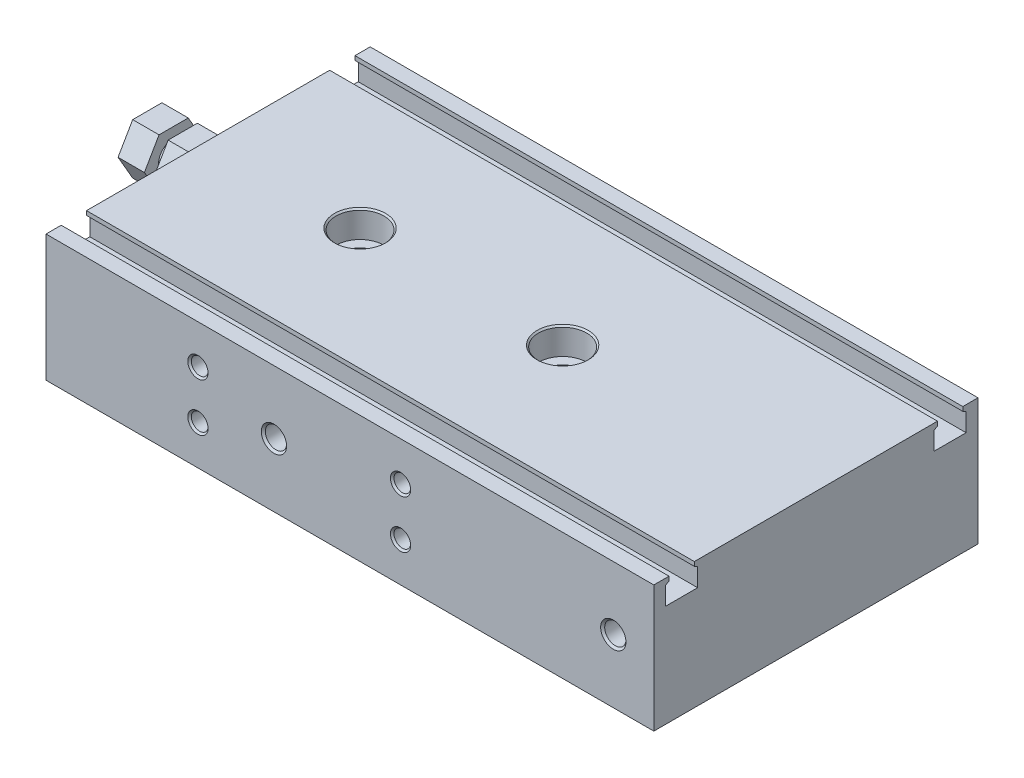
SolidWorks part; units mm, degrees
ref_plane "Plane1" through (0, 0, 0) normal (0, 0, 1) x (1, 0, 0)
ref_plane "Plane2" through (0, 0, 0) normal (0, 1, 0) x (1, 0, 0)
ref_plane "Plane3" through (0, 0, 0) normal (1, 0, 0) x (0, 0, -1)
sketch "Body_Sketch" plane through (0, 0, 0) normal (1, 0, 0) x (0, 0, -1)
  line L0 (-32, 12.5) -> (-32, -12.5)
  line L1 (-32, -12.5) -> (32, -12.5)
  line L2 (32, -12.5) -> (32, 12.5)
  line L3 (32, 12.5) -> (-32, 12.5)
  line L4 (-25.3, 0) -> (25.3, 0) construction
  line L5 (0, -7.85) -> (0, 10.85) construction
  line L6 (27.956, 0) -> (-27.956, 0) construction
  line L7 (0, 12.3416) -> (0, -12.3416) construction
  dimension "A" = 64
  dimension "B" = 25
  dimension "QQ" = 12.5
extrude "Body" add sketch "Body_Sketch" along normal blind 120
sketch "Body Bot Grooves_Sketch" [suppressed] plane through (0, 0, 0) normal (1, 0, 0) x (0, 0, -1)
  line L0 (0, 0) -> (0, -14.4793) construction
  line L1 (-12, -6.5) -> (-4, -6.5)
  line L2 (-4, -6.5) -> (-5, -5.5)
  line L3 (-5, -5.5) -> (-11, -5.5)
  line L4 (-11, -5.5) -> (-12, -6.5)
  line L5 (-8, -5.5) -> (-8, -12.5787) construction
  line L6 (18.5, 10) -> (-18.5, 10) construction
  line L7 (11, -5.5) -> (12, -6.5)
  line L8 (5, -5.5) -> (11, -5.5)
  line L9 (4, -6.5) -> (5, -5.5)
  line L10 (12, -6.5) -> (4, -6.5)
  dimension "Angle" = 45
  dimension "Raw Height" = 16.5
  dimension "Loc Y" = 15.5
  dimension "Width" = 8
  dimension "C2C" = 16
extrude "Body Bot Grooves" [suppressed] cut sketch "Body Bot Grooves_Sketch" along normal through all
sketch "Body Rod Holes_Sketch" plane through (0, 0, 0) normal (-1, 0, 0) x (0, 0, 1)
  line L0 (27.956, 0) -> (-27.956, 0) construction
  line L1 (0, 11.1009) -> (0, -8.2638) construction
  line L2 (0, -12.3416) -> (0, 12.3416) construction
  circle A0 centre (-14, 0) radius 5
  circle A1 centre (14, 0) radius 5
  dimension "NN" = 10
  dimension "H" = 28
extrude "Body Rod Holes" cut sketch "Body Rod Holes_Sketch" against normal blind 10
sketch "Body Piston Holes_Sketch" plane through (10, 0, 0) normal (-1, 0, 0) x (0, 0, 1)
  circle A0 centre (14, 0) radius 6.05
  circle A1 centre (-14, 0) radius 6.05
extrude "Body Piston Holes" cut sketch "Body Piston Holes_Sketch" against normal blind 51
sketch "Body Thru Hole_Sketch" [suppressed] plane through (0, 0, 0) normal (1, 0, 0) x (0, 0, -1)
  line L0 (0, 0) -> (0, -9.4152) construction
  line L1 (11.5, -6) -> (18.5, -6) construction
  circle A0 centre (14.95, -3) radius 1.4
  dimension "Dia" = 2.8
  dimension "Loc Y" = 3
  dimension "Loc Z" = 14.95
extrude "Body Thru Hole" [suppressed] cut sketch "Body Thru Hole_Sketch" along normal through all
sketch "Bot Switch Groove_Sketch" [suppressed] plane through (0, 0, 0) normal (1, 0, 0) x (0, 0, -1)
  line L0 (0, 0) -> (0, -12.0384) construction
  line L1 (1.6, -6.5) -> (-1.6, -6.5)
  line L2 (-1.6, -6.5) -> (-1.6, -3)
  line L3 (-1.6, -3) -> (-2.8, -3)
  line L4 (-2.8, -3) -> (-2.8, 0)
  line L5 (-2.8, 0) -> (2.8, 0)
  line L6 (2.8, -3) -> (2.8, 0)
  line L7 (-12, -6.5) -> (-4, -6.5) construction
  line L8 (1.6, -3) -> (2.8, -3)
  line L10 (1.6, -6.5) -> (1.6, -3)
  point P12 (0, 0)
  point P15 (0, -6.5)
  dimension "Bot Height" = 3.5
  dimension "Top Height" = 3
  dimension "Bot Width" = 3.2
  dimension "Top Width" = 5.6
extrude "Bot Switch Groove" [suppressed] cut sketch "Bot Switch Groove_Sketch" along normal through all
sketch "Top Switch Grooves_Sketch" plane through (0, 0, 0) normal (-1, 0, 0) x (0, 0, 1)
  line L0 (0, -12.3416) -> (0, 12.3416) construction
  line L1 (26.5, 4.6906) -> (26.5, 11.0706) construction
  line L2 (-32, 12.5) -> (32, 12.5) construction
  line L3 (23.35, 7.7) -> (29.65, 7.7)
  line L4 (-23.35, 11.3) -> (-23.35, 7.7)
  line L5 (-23.35, 7.7) -> (-29.65, 7.7)
  line L6 (-29.65, 7.7) -> (-29.65, 11.3)
  line L7 (-29, 12.5) -> (-24, 12.5)
  line L8 (29.65, 7.7) -> (29.65, 11.3)
  line L9 (29, 11.6753) -> (29.65, 11.3)
  line L10 (29, 12.5) -> (29, 11.6753)
  line L11 (29, 12.5) -> (24, 12.5)
  line L12 (-29, 12.5) -> (-29, 11.6753)
  line L13 (-24, 12.5) -> (-24, 11.6753)
  line L14 (-24, 11.6753) -> (-23.35, 11.3)
  line L15 (-29, 11.6753) -> (-29.65, 11.3)
  line L16 (0, 4.91) -> (0, 11.29) construction
  line L17 (24, 12.5) -> (24, 11.6753)
  line L18 (-26.5, 4.91) -> (-26.5, 11.29) construction
  line L19 (24, 11.6753) -> (23.35, 11.3)
  line L20 (23.35, 11.3) -> (23.35, 7.7)
  point P4 (-26.5, 12.5)
  point P12 (26.5, 12.5)
  dimension "Bot Width" = 6.3
  dimension "Top Width" = 5
  dimension "P" = 53
  dimension "Bot Height" = 3.6
  dimension "Angle" = 120
  dimension "Depth" = 4.8
extrude "Top Switch Grooves" cut sketch "Top Switch Grooves_Sketch" against normal through all
sketch "SHCS MGT Hole_Sketch" plane through (0, 0, 0) normal (0, 0, 1) x (1, 0, 0)
  line L0 (30, 12.5) -> (25.25, 12.5)
  line L1 (25.25, 12.5) -> (25.25, 7.2)
  line L2 (25.25, 7.2) -> (27.25, 7.2)
  line L3 (27.25, 7.2) -> (27.25, -12.5)
  line L4 (27.25, -12.5) -> (30, -12.5)
  line L5 (30, -12.5) -> (30, 12.5)
  line L6 (30, -11.5069) -> (30, 12.6548) construction
  line L7 (120, 12.5) -> (0, 12.5) construction
  line L8 (120, -12.5) -> (0, -12.5) construction
  line L9 (0, -12.5712) -> (0, 12.5712) construction
  dimension "M_depth" = 5.3
  dimension "M" = 9.5
  dimension "U" = 5.5
  dimension "L" = 30
revolve "SHCS MGT Hole" cut sketch "SHCS MGT Hole_Sketch" angle 360 about L6
chamfer "SHCS MGT Hole Cham" distance 0.3 1 edges at (30, 12.5, -4.75)
pattern_linear "SHCS MGT Hole Pat" count 2 spacing 40 along (1, 0, 0) of "SHCS MGT Hole", "SHCS MGT Hole Cham"
hole_wizard "SHCS MGT Hole Bot Tap" positions "SHCS MGT Hole Bot Tap Loc" profile "SHCS MGT Hole Bot Tap Profile" tap size "M4x0.7" standard "Ansi Metric"
sketch "SHCS MGT Hole Bot Tap Loc" plane through (0, -12.5, 0) normal (0, -1, 0) x (1, 0, 0)
  circle A0 centre (70, 0) radius 2.75 construction
  circle A1 centre (30, 0) radius 2.75 construction
  point P0 (30, 0)
  point P1 (70, 0)
sketch "SHCS MGT Hole Bot Tap Profile" plane through (30, -12.5, 0) normal (1, 0, 0) x (0, 0, -1)
  line L0 (0, 0) -> (0, 12.6524)
  line L1 (0, 12.6524) -> (2.75, 11)
  line L2 (2.75, 11) -> (2.75, 10)
  line L3 (2.75, 10) -> (3, 10)
  line L5 (3, 10) -> (3, 0.3)
  line L6 (3, 0.3) -> (3.3, 0)
  line L7 (3.3, 0) -> (0, 0)
  line L8 (-3, 0.3) -> (-3.3, 0) construction
  line L10 (0, 12.6524) -> (-2.75, 11) construction
  line L11 (0, -6.35) -> (0, 107.95) construction
  dimension "Tap Drill Dia." = 5.5
  dimension "Tap Drill Depth" = 11
  dimension "Thread Major Dia." = 6
  dimension "Thread Depth" = 10
  dimension "Near CSink Dia." = 6.6
  dimension "Near CSink Angle" = 90
  dimension "Drill Angle" = 118
sketch "Adjuster Nut_Sketch" plane through (0, 0, 0) normal (-1, 0, 0) x (0, 0, 1)
  line L0 (-2.8868, 11.5) -> (2.8868, 11.5)
  line L1 (2.8868, 11.5) -> (5.7735, 6.5)
  line L2 (2.8868, 1.5) -> (5.7735, 6.5)
  line L3 (2.8868, 1.5) -> (-2.8868, 1.5)
  line L4 (-5.7735, 6.5) -> (-2.8868, 1.5)
  line L5 (-2.8868, 11.5) -> (-5.7735, 6.5)
  line L6 (0, -12.3416) -> (0, 12.3416) construction
  line L7 (27.956, 0) -> (-27.956, 0) construction
  line L8 (-4.4456, 6.5) -> (4.4456, 6.5) construction
  line L10 (0, 1.15) -> (0, 8.85) construction
  circle A0 centre (0, 6.5) radius 5 construction
  dimension "OO_keyw" = 10
  dimension "TT" = 6.5
extrude "Adjuster Nut" add sketch "Adjuster Nut_Sketch" along normal blind 12
sketch "Adjuster Nut Threads_Sketch" plane through (0, 0, 0) normal (0, 0, 1) x (1, 0, 0)
  line L0 (-6.8, 34.5) -> (-6.8, 9.5)
  line L1 (-6.8, 9.5) -> (-5, 9.5)
  line L2 (-5, 9.5) -> (-5, 34.5)
  line L3 (-5, 34.5) -> (-6.8, 34.5)
  line L4 (-6.476, 6.5) -> (-3.044, 6.5) construction
  line L5 (-12, 6.5) -> (0, 6.5) construction
  line L6 (0, -12.5712) -> (0, 12.5712) construction
  line L7 (-12, 6.5) -> (-12, 11.5) construction
  line L8 (0, 12.5) -> (0, -12.5) construction
  dimension "OO" = 6
  dimension "Nut Thickness Body" = 5
  dimension "Nut Thickness Plate" = 5.2
revolve "Adjuster Nut Threads" cut sketch "Adjuster Nut Threads_Sketch" angle 360 about L4
hole_wizard "Tap Drill for M5x0.8 Tap1" positions "Sketch2" profile "Sketch1" hole size "M5x0.8" standard "ANSI Metric"
sketch "Sketch2" plane through (0, 0, 32) normal (0, 0, 1) x (1, 0, 0)
  line L0 (120, -12.5) -> (0, -12.5) construction
  line L1 (120, 12.5) -> (120, -12.5) construction
  line L2 (0, 12.5) -> (0, -12.5) construction
  point P0 (45, 0)
  point P2 (112, 0)
  dimension "D1" = 12.5
  dimension "D2" = 8
  dimension "D3" = 45
sketch "Sketch1" plane through (45, 0, 32) normal (1, 0, 0) x (0, -1, 0)
  line L0 (0, 0) -> (0, 5.7618)
  line L1 (0, 5.7618) -> (2.1, 4.5)
  line L2 (2.1, 4.5) -> (2.1, 0.4)
  line L3 (2.1, 0.4) -> (2.5, 0)
  line L5 (2.5, 0) -> (0, 0)
  line L6 (-2.1, 0.4) -> (-2.5, 0) construction
  line L10 (0, 5.7618) -> (-2.1, 4.5) construction
  line L11 (0, -6.35) -> (0, 107.95) construction
  dimension "Hole Dia." = 4.2
  dimension "Hole Depth" = 4.5
  dimension "Near C'Sink Dia." = 5
  dimension "Near C'Sink Angle" = 90
  dimension "Drill Angle" = 118
hole_wizard "Tap Drill for M5x0.8 Tap2" positions "Sketch4" profile "Sketch3" hole size "M5x0.8" standard "ANSI Metric"
sketch "Sketch4" plane through (0, 0, -32) normal (0, 0, -1) x (-1, 0, 0)
  line L0 (-120, -12.5) -> (-120, 12.5) construction
  line L1 (0, -12.5) -> (0, 12.5) construction
  line L2 (-120, -12.5) -> (0, -12.5) construction
  point P0 (-112, 0)
  point P2 (-45, 0)
  dimension "D1" = 8
  dimension "D2" = 45
  dimension "D3" = 12.5
sketch "Sketch3" plane through (112, 0, -32) normal (1, 0, 0) x (0, 1, 0)
  line L0 (0, 0) -> (0, 5.7618)
  line L1 (0, 5.7618) -> (2.1, 4.5)
  line L2 (2.1, 4.5) -> (2.1, 0.4)
  line L3 (2.1, 0.4) -> (2.5, 0)
  line L5 (2.5, 0) -> (0, 0)
  line L6 (-2.1, 0.4) -> (-2.5, 0) construction
  line L10 (0, 5.7618) -> (-2.1, 4.5) construction
  line L11 (0, -6.35) -> (0, 107.95) construction
  dimension "Hole Dia." = 4.2
  dimension "Hole Depth" = 4.5
  dimension "Near C'Sink Dia." = 5
  dimension "Near C'Sink Angle" = 90
  dimension "Drill Angle" = 118
hole_wizard "Mount_Holes_1" positions "Sketch6" profile "Sketch5" hole size "M3x0.5" standard "ANSI Metric"
sketch "Sketch6" plane through (0, 0, 32) normal (0, 0, 1) x (1, 0, 0)
  line L0 (120, -12.5) -> (0, -12.5) construction
  line L1 (0, 12.5) -> (0, -12.5) construction
  point P0 (30, -4.75)
  point P2 (70, -4.75)
  dimension "D1" = 7.75
  dimension "D2" = 30
  dimension "D3" = 40
sketch "Sketch5" plane through (30, -4.75, 32) normal (1, 0, 0) x (0, -1, 0)
  line L0 (0, 0) -> (0, 6.4914)
  line L1 (0, 6.4914) -> (1.65, 5.5)
  line L2 (1.65, 5.5) -> (1.65, 0.35)
  line L3 (1.65, 0.35) -> (2, 0)
  line L5 (2, 0) -> (0, 0)
  line L6 (-1.65, 0.35) -> (-2, 0) construction
  line L10 (0, 6.4914) -> (-1.65, 5.5) construction
  line L11 (0, -6.35) -> (0, 107.95) construction
  dimension "Hole Dia." = 3.3
  dimension "Hole Depth" = 5.5
  dimension "Near C'Sink Dia." = 4
  dimension "Near C'Sink Angle" = 90
  dimension "Drill Angle" = 118
hole_wizard "Mount_Holes_2" positions "Sketch8" profile "Sketch7" hole size "M3x0.5" standard "ANSI Metric"
sketch "Sketch8" plane through (0, 0, -32) normal (0, 0, -1) x (-1, 0, 0)
  line L0 (-120, -12.5) -> (0, -12.5) construction
  line L1 (0, -12.5) -> (0, 12.5) construction
  point P0 (-70, -4.75)
  point P2 (-30, -4.75)
  dimension "D1" = 7.75
  dimension "D2" = 30
  dimension "D3" = 40
sketch "Sketch7" plane through (70, -4.75, -32) normal (1, 0, 0) x (0, 1, 0)
  line L0 (0, 0) -> (0, 6.4914)
  line L1 (0, 6.4914) -> (1.65, 5.5)
  line L2 (1.65, 5.5) -> (1.65, 0.35)
  line L3 (1.65, 0.35) -> (2, 0)
  line L5 (2, 0) -> (0, 0)
  line L6 (-1.65, 0.35) -> (-2, 0) construction
  line L10 (0, 6.4914) -> (-1.65, 5.5) construction
  line L11 (0, -6.35) -> (0, 107.95) construction
  dimension "Hole Dia." = 3.3
  dimension "Hole Depth" = 5.5
  dimension "Near C'Sink Dia." = 4
  dimension "Near C'Sink Angle" = 90
  dimension "Drill Angle" = 118
hole_wizard "Mount_Holes_3" positions "Sketch10" profile "Sketch9" hole size "M4x0.7" standard "ANSI Metric"
sketch "Sketch10" plane through (0, 0, 32) normal (0, 0, 1) x (1, 0, 0)
  line L0 (120, 12.5) -> (0, 12.5) construction
  line L1 (0, 12.5) -> (0, -12.5) construction
  point P0 (30, 4.75)
  point P2 (70, 4.75)
  dimension "D1" = 7.75
  dimension "D2" = 30
  dimension "D3" = 40
sketch "Sketch9" plane through (30, 4.75, 32) normal (1, 0, 0) x (0, -1, 0)
  line L0 (0, 0) -> (0, 6.4914)
  line L1 (0, 6.4914) -> (1.65, 5.5)
  line L2 (1.65, 5.5) -> (1.65, 0.35)
  line L3 (1.65, 0.35) -> (2, 0)
  line L5 (2, 0) -> (0, 0)
  line L6 (-1.65, 0.35) -> (-2, 0) construction
  line L10 (0, 6.4914) -> (-1.65, 5.5) construction
  line L11 (0, -6.35) -> (0, 107.95) construction
  dimension "Hole Dia." = 3.3
  dimension "Hole Depth" = 5.5
  dimension "Near C'Sink Dia." = 4
  dimension "Near C'Sink Angle" = 90
  dimension "Drill Angle" = 118
hole_wizard "Mount_Holes_4" positions "Sketch12" profile "Sketch11" hole size "M4x0.7" standard "ANSI Metric"
sketch "Sketch12" plane through (0, 0, -32) normal (0, 0, -1) x (-1, 0, 0)
  line L1 (-120, 12.5) -> (0, 12.5) construction
  line L2 (0, -12.5) -> (0, 12.5) construction
  point P0 (-70, 4.75)
  point P2 (-30, 4.75)
  dimension "D1" = 7.75
  dimension "D2" = 30
  dimension "D3" = 40
sketch "Sketch11" plane through (70, 4.75, -32) normal (1, 0, 0) x (0, 1, 0)
  line L0 (0, 0) -> (0, 6.4914)
  line L1 (0, 6.4914) -> (1.65, 5.5)
  line L2 (1.65, 5.5) -> (1.65, 0.35)
  line L3 (1.65, 0.35) -> (2, 0)
  line L5 (2, 0) -> (0, 0)
  line L6 (-1.65, 0.35) -> (-2, 0) construction
  line L10 (0, 6.4914) -> (-1.65, 5.5) construction
  line L11 (0, -6.35) -> (0, 107.95) construction
  dimension "Hole Dia." = 3.3
  dimension "Hole Depth" = 5.5
  dimension "Near C'Sink Dia." = 4
  dimension "Near C'Sink Angle" = 90
  dimension "Drill Angle" = 118
hole_wizard "1/8 Rc Tapped Hole1" positions "Sketch14" profile "Sketch13" size "1/8" standard "ISO"
sketch "Sketch14" plane through (0, 0, 49) normal (0, 0, 1) x (1, 0, 0)
  line L0 (182, -19) -> (0, -19) construction
  line L1 (0, 19) -> (0, -19) construction
  line L2 (182, 19) -> (182, -19) construction
  point P0 (56, 0)
  point P2 (172, 0)
  dimension "D1" = 15
  dimension "D2" = 46
  dimension "D3" = 9
sketch "Sketch13" plane through (56, 0, 49) normal (1, 0, 0) x (0, -1, 0)
  line L0 (0, 0) -> (0, 11.4134)
  line L1 (3.95, 9.04) -> (0, 11.4134)
  line L2 (-3.95, 9.04) -> (0, 11.4134) construction
  line L3 (3.95, 9.04) -> (3.95, 4.5)
  line L4 (3.95, 4.5) -> (4.633, 4.5)
  line L5 (4.633, 4.5) -> (4.7735, 0)
  line L6 (-4.633, 4.5) -> (-4.7735, 0) construction
  line L7 (4.7735, 0) -> (0, 0)
  line L8 (0, -6.35) -> (0, 107.95) construction
  line L11 (-3.95, 4.5) -> (-4.633, 4.5) construction
  dimension "Tap Drill Dia." = 7.9
  dimension "Tap Drill Depth" = 9.04
  dimension "Thread Dia." = 9.5469
  dimension "Thread Angle" = 3.576
  dimension "Thread Depth" = 4.5
  dimension "Drill Angle" = 118
hole_wizard "1/8 Rc Tapped Hole2" positions "Sketch16" profile "Sketch15" size "1/8" standard "ISO"
sketch "Sketch16" plane through (0, 0, -49) normal (0, 0, -1) x (-1, 0, 0)
  line L0 (-182, -19) -> (0, -19) construction
  line L1 (0, -19) -> (0, 19) construction
  line L2 (-182, -19) -> (-182, 19) construction
  point P0 (-172, 0)
  point P2 (-56, 0)
  dimension "D1" = 15
  dimension "D2" = 46
  dimension "D3" = 9
sketch "Sketch15" plane through (172, 0, -49) normal (1, 0, 0) x (0, 1, 0)
  line L0 (0, 0) -> (0, 11.4134)
  line L1 (3.95, 9.04) -> (0, 11.4134)
  line L2 (-3.95, 9.04) -> (0, 11.4134) construction
  line L3 (3.95, 9.04) -> (3.95, 4.5)
  line L4 (3.95, 4.5) -> (4.633, 4.5)
  line L5 (4.633, 4.5) -> (4.7735, 0)
  line L6 (-4.633, 4.5) -> (-4.7735, 0) construction
  line L7 (4.7735, 0) -> (0, 0)
  line L8 (0, -6.35) -> (0, 107.95) construction
  line L11 (-3.95, 4.5) -> (-4.633, 4.5) construction
  dimension "Tap Drill Dia." = 7.9
  dimension "Tap Drill Depth" = 9.04
  dimension "Thread Dia." = 9.5469
  dimension "Thread Angle" = 3.576
  dimension "Thread Depth" = 4.5
  dimension "Drill Angle" = 118
